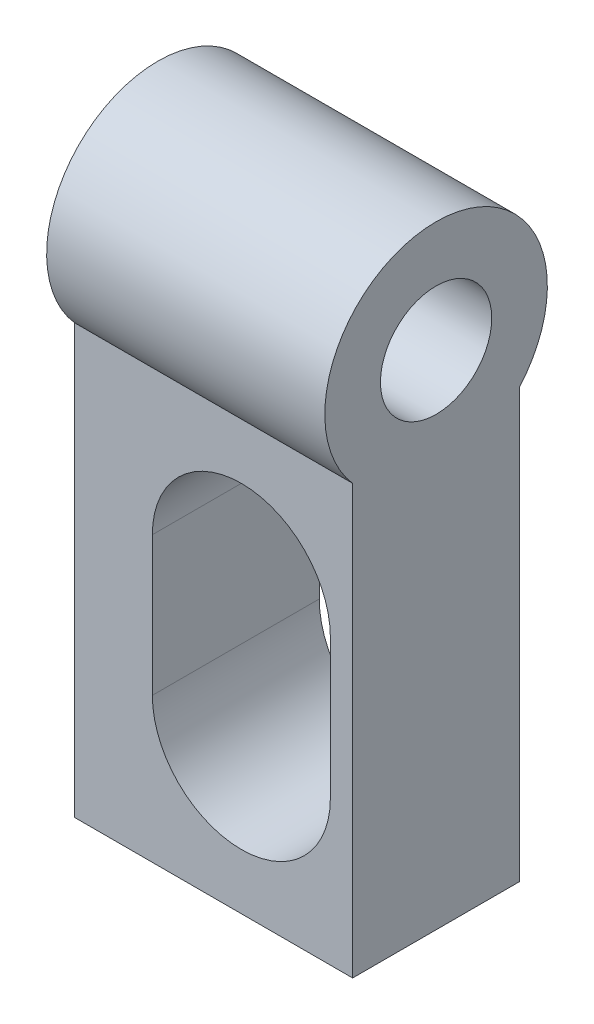
SolidWorks part; units mm, degrees
ref_plane "Front Plane" through (0, 0, 0) normal (0, 0, 1) x (1, 0, 0)
ref_plane "Top Plane" through (0, 0, 0) normal (0, 1, 0) x (1, 0, 0)
ref_plane "Right Plane" through (0, 0, 0) normal (1, 0, 0) x (0, 0, -1)
sketch "Sketch1" plane through (0, 0, 0) normal (1, 0, 0) x (0, 0, -1)
  line L0 (0, 7.7) -> (0, 0)
  line L1 (0, 0) -> (3, 0)
  line L2 (3, 0) -> (3, 7.7)
  circle A0 centre (1.5, 9.0229) radius 1
  arc A1 (0, 7.7) -> (3, 7.7) centre (1.5, 9.0229) cw
  dimension "D3" = 2
  dimension "D1" = 3
  dimension "D2" = 7.7
  dimension "D4" = 2
  dimension "D5" = 1.5
extrude "Boss-Extrude1" add sketch "Sketch1" along normal blind 5 contours A1 L0 L1 L2 A0
sketch "Sketch2" plane through (0, 0, -3) normal (0, 0, -1) x (-1, 0, 0)
  line L0 (-2, 5.1) -> (-2, 2.6) construction
  line L1 (-0.4, 5.1) -> (-0.4, 2.6)
  line L2 (-3.6, 5.1) -> (-3.6, 2.6)
  line L3 (0, 0) -> (0, 7.7) construction
  line L4 (-5, 0) -> (0, 0) construction
  arc A0 (-0.4, 5.1) -> (-3.6, 5.1) centre (-2, 5.1) ccw
  arc A1 (-3.6, 2.6) -> (-0.4, 2.6) centre (-2, 2.6) ccw
  point P2 (-2, 3.85)
  dimension "D1" = 1.6
  dimension "D2" = 2.5
  dimension "D3" = 2
  dimension "D4" = 3.85
extrude "Cut-Extrude1" cut sketch "Sketch2" against normal through all
mirror "Mirror1" about plane through (5, 0, 0) normal (1, 0, 0) of "Cut-Extrude1", "Boss-Extrude1"
sketch "Sketch3" plane through (0, 0, 0) normal (-1, 0, 0) x (0, 0, 1)
  line L1 (-5.3722, 12.6649) -> (2.5502, 12.6649)
  line L2 (-5.3722, 12.6649) -> (-5.3722, -0.91)
  line L3 (-5.3722, -0.91) -> (2.5502, -0.91)
  line L4 (2.5502, 12.6649) -> (2.5502, -0.91)
extrude "Cut-Extrude2" cut sketch "Sketch3" against normal blind 5
